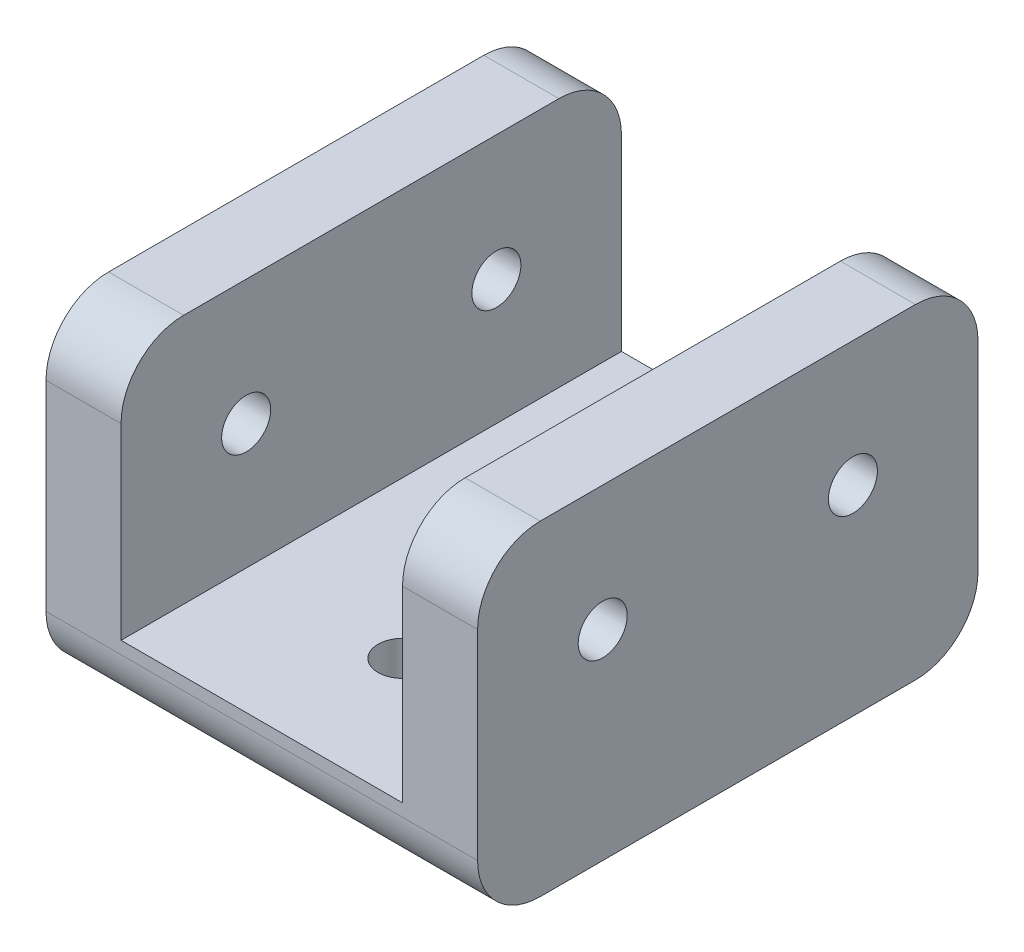
SolidWorks part; units mm, degrees
material "PET"
ref_plane "Front Plane" through (0, 0, 0) normal (0, 0, 1) x (1, 0, 0)
ref_plane "Top Plane" through (0, 0, 0) normal (0, 1, 0) x (1, 0, 0)
ref_plane "Right Plane" through (0, 0, 0) normal (1, 0, 0) x (0, 0, -1)
sketch "Sketch1" plane through (0, 0, 0) normal (0, 0, 1) x (1, 0, 0)
  line L0 (10.795, 33.02) -> (10.795, 7.62) construction
  line L1 (0, 0) -> (43.815, 0)
  line L2 (0, 0) -> (0, 33.02)
  line L3 (0, 33.02) -> (43.815, 33.02)
  line L4 (43.815, 0) -> (43.815, 33.02)
  line L5 (7.62, 33.02) -> (36.195, 33.02)
  line L6 (7.62, 33.02) -> (7.62, 7.62)
  line L7 (7.62, 7.62) -> (36.195, 7.62)
  line L8 (36.195, 33.02) -> (36.195, 7.62)
  dimension "D1" = 33.02
  dimension "D2" = 25.4
  dimension "D3" = 28.575
  dimension "D4" = 7.62
  dimension "D5" = 7.62
  dimension "D6" = 25.4
extrude "Boss-Extrude1" add sketch "Sketch1" against normal blind 50.8 contours L3 L8 L7 L6 L2 L1 L4
fillet "Fillet1" radius 6.35 6 edges at (40.005, 33.02, -50.8) (40.005, 33.02, 0) (21.9075, 0, 0) (21.9075, 0, -50.8) (3.81, 33.02, 0) (3.81, 33.02, -50.8)
sketch "Sketch2" plane through (0, 0, 0) normal (-1, 0, 0) x (0, 0, 1)
  line L0 (-44.45, 33.02) -> (-6.35, 33.02) construction
  line L1 (-50.8, 6.35) -> (-50.8, 26.67) construction
  circle A0 centre (-38.1, 20.32) radius 2.4892
  circle A1 centre (-12.7, 20.32) radius 2.4892
  dimension "D1" = 4.9784
  dimension "D2" = 12.7
  dimension "D3" = 12.7
  dimension "D4" = 2
extrude "Cut-Extrude1" cut sketch "Sketch2" against normal through all
sketch "Sketch3" plane through (0, 0, 0) normal (0, -1, 0) x (1, 0, 0)
  line L0 (10.795, 0) -> (10.795, -50.8) construction
  line L2 (0, 0) -> (43.815, 0) construction
  line L6 (43.815, -50.8) -> (0, -50.8) construction
  line L7 (0, -44.45) -> (0, -6.35) construction
  line L8 (43.815, -44.45) -> (43.815, -6.35) construction
  circle A0 centre (23.495, -38.1) radius 2.4892
  circle A1 centre (23.495, -12.7) radius 2.4892
  dimension "D1" = 4.9784
  dimension "D2" = 10.795
  dimension "D4" = 20.32
  dimension "D3" = 2
extrude "Cut-Extrude2" cut sketch "Sketch3" against normal through all
